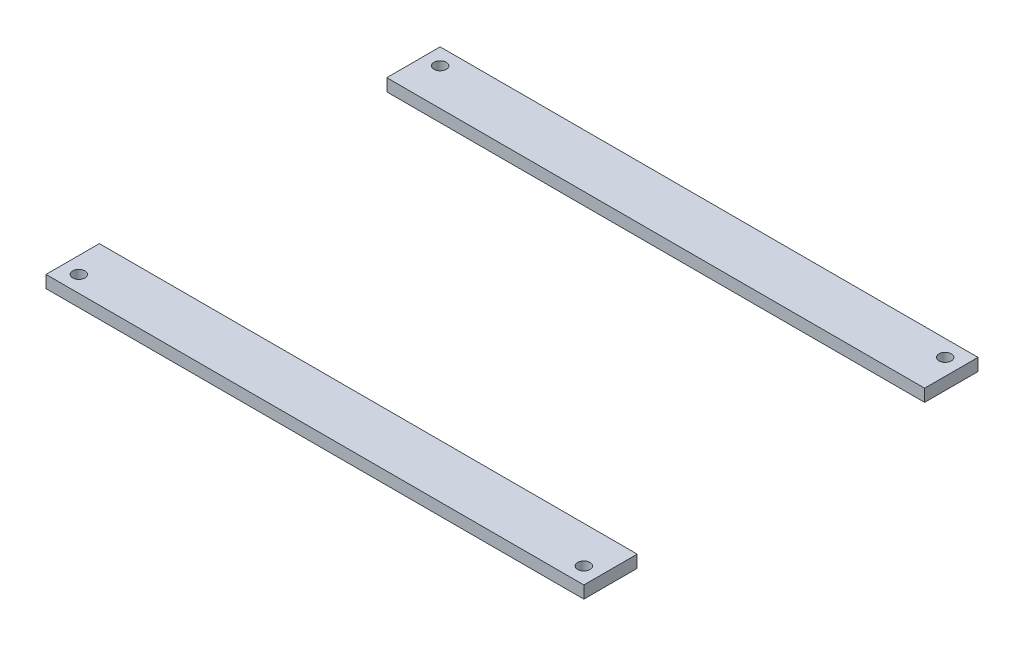
SolidWorks part; units mm, degrees
ref_plane "Front Plane" through (0, 0, 0) normal (0, 0, 1) x (1, 0, 0)
ref_plane "Top Plane" through (0, 0, 0) normal (0, 1, 0) x (1, 0, 0)
ref_plane "Right Plane" through (0, 0, 0) normal (1, 0, 0) x (0, 0, -1)
sketch "Sketch1" plane through (0, 0, 0) normal (0, 1, 0) x (1, 0, 0)
  line L0 (0, 48) -> (0, -48) construction
  line L1 (65.5, -48) -> (-65.5, -48)
  line L2 (65.5, -48) -> (65.5, 48)
  line L3 (65.5, 48) -> (-65.5, 48)
  line L4 (-65.5, -48) -> (-65.5, 48)
  line L5 (65.5, -48) -> (-65.5, 48) construction
  line L6 (65.5, 48) -> (-65.5, -48) construction
  line L7 (-65.5, 0) -> (65.5, 0) construction
  line L8 (-65.5, 35) -> (65.5, 35)
  line L9 (-65.5, -35) -> (65.5, -35)
  circle A0 centre (-61.5, 44) radius 1.5
  circle A1 centre (61.5, 44) radius 1.5
  circle A2 centre (-61.5, -44) radius 1.5
  circle A3 centre (61.5, -44) radius 1.5
  point P0 (0, 0)
  dimension "D3" = 3
  dimension "D1" = 131
  dimension "D2" = 96
  dimension "D4" = 4
  dimension "D5" = 4
  dimension "D6" = 13
  dimension "D7" = 13
extrude "Boss-Extrude1" add sketch "Sketch1" along normal mid plane 3 contours L9 L4 L1 L2 A3 A2 | L4 L8 L2 L3 A0 A1
